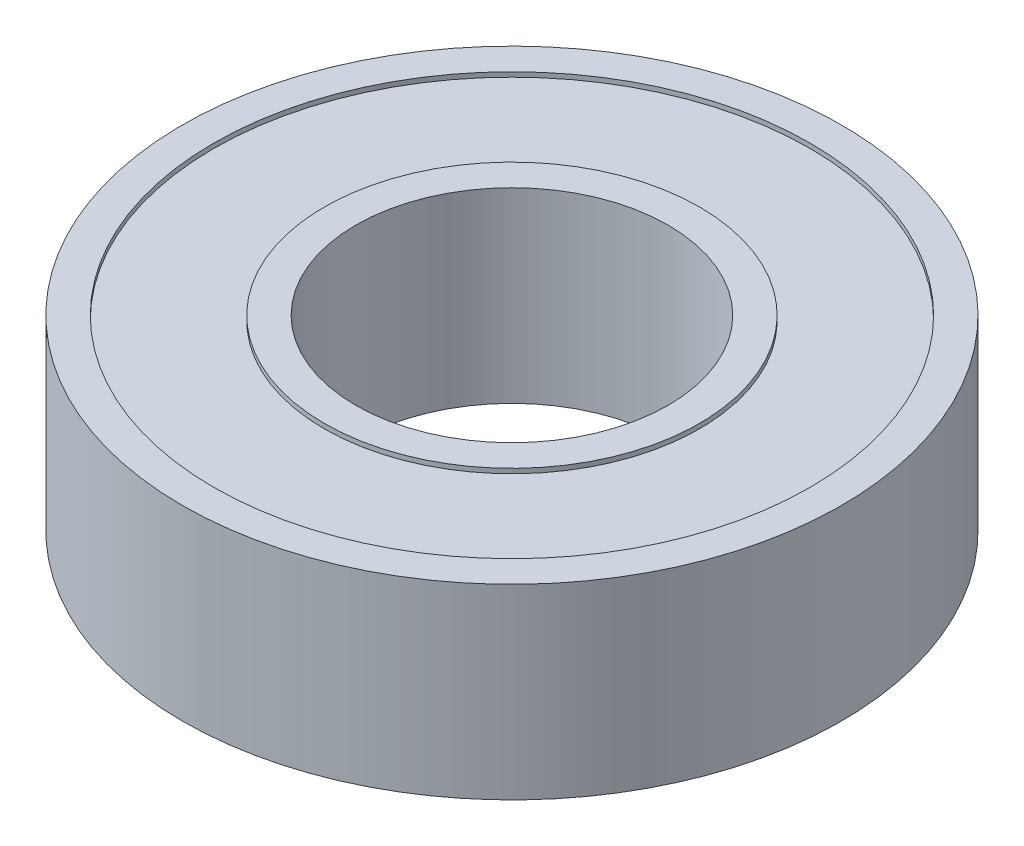
SolidWorks part; units mm, degrees
ref_plane "Спереди" through (0, 0, 0) normal (0, 0, 1) x (1, 0, 0)
ref_plane "Сверху" through (0, 0, 0) normal (0, 1, 0) x (1, 0, 0)
ref_plane "Справа" through (0, 0, 0) normal (1, 0, 0) x (0, 0, -1)
sketch "Эскиз1" plane through (0, 0, 0) normal (0, 1, 0) x (1, 0, 0)
  circle A0 centre (0, 0) radius 9.95
  circle A1 centre (0, 0) radius 21
  dimension "D1" = 19.9
  dimension "D2" = 42
extrude "Бобышка-Вытянуть1" add sketch "Эскиз1" along normal mid plane 11.9
sketch "Эскиз2" plane through (0, 5.95, 0) normal (0, 1, 0) x (1, 0, 0)
  circle A0 centre (0, 0) radius 11.95
  circle A1 centre (0, 0) radius 19
  circle A2 centre (0, 0) radius 21 construction
  circle A3 centre (0, 0) radius 9.95 construction
  dimension "D1" = 2
  dimension "D2" = 2
extrude "Вырез-Вытянуть1" cut sketch "Эскиз2" against normal blind 0.3
mirror "Зеркальное отражение1" about plane through (0, 0, 0) normal (0, 1, 0) of "Вырез-Вытянуть1"
equation "\"big_bearing_d1\"= 19.9"
equation "\"big_bearing_d2\"= 42"
equation "\"big_bearing_h\"= 11.9"
equation "\"print_offset\"= 0.5"
equation "\"small_bearing_d1\"= 2.9"
equation "\"small_bearing_d2\"= 10"
equation "\"small_bearing_h\"= 4"
equation "\"tube_d\"= 16"
equation "\"small_bearing_distance\"= 2"
equation "\"D2@Эскиз1\"=\"big_bearing_d2\""
equation "\"D1@Бобышка-Вытянуть1\"=\"big_bearing_h\""
